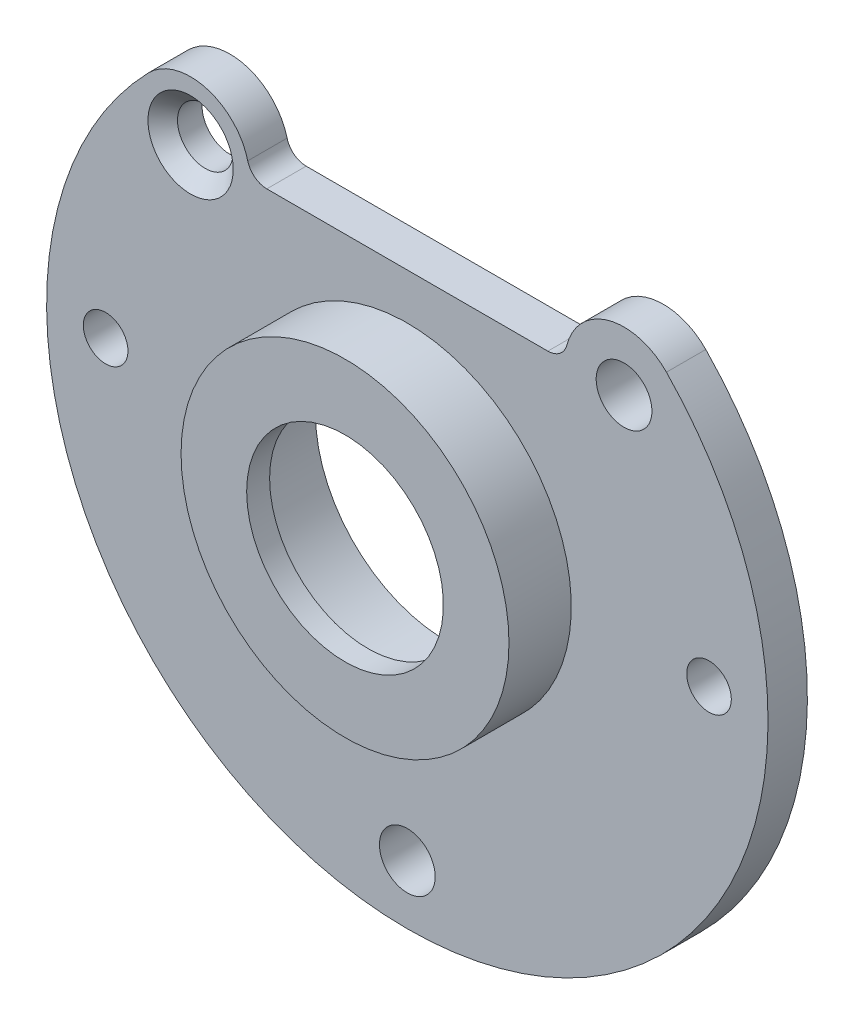
SolidWorks part; units mm, degrees
ref_plane "前视基准面" through (0, 0, 0) normal (0, 0, 1) x (1, 0, 0)
ref_plane "上视基准面" through (0, 0, 0) normal (0, 1, 0) x (1, 0, 0)
ref_plane "右视基准面" through (0, 0, 0) normal (1, 0, 0) x (0, 0, -1)
sketch "草图1" plane through (0, 0, 0) normal (0, 0, 1) x (1, 0, 0)
  line L0 (0, 0) -> (33.0454, 32) construction
  line L1 (0, 0) -> (0, 24.5594) construction
  line L2 (0, -55) -> (0, 55) construction
  line L3 (0, 0) -> (-33.0454, 32) construction
  line L4 (21.4265, 32) -> (-21.4265, 32)
  line L5 (55, 0) -> (-55, 0) construction
  arc A0 (-39.5108, 38.2609) -> (39.5108, 38.2609) centre (0, 0) ccw
  circle A1 centre (0, 0) radius 46 construction
  arc A2 (39.5108, 38.2609) -> (24.3312, 34.25) centre (33.0454, 32) ccw
  arc A3 (-39.5108, 38.2609) -> (-24.3312, 34.25) centre (-33.0454, 32) cw
  arc A4 (-26.58, 25.7391) -> (-38.6438, 24.9531) centre (-33.0454, 32) cw construction
  arc A5 (-38.6438, 24.9531) -> (-39.5108, 38.2609) centre (-33.0454, 32) cw construction
  arc A6 (-24.0454, 32) -> (-26.58, 25.7391) centre (-33.0454, 32) cw construction
  arc A7 (24.0454, 32) -> (26.58, 25.7391) centre (33.0454, 32) ccw construction
  arc A8 (26.58, 25.7391) -> (38.6438, 24.9531) centre (33.0454, 32) ccw construction
  arc A9 (38.6438, 24.9531) -> (39.5108, 38.2609) centre (33.0454, 32) ccw construction
  arc A10 (39.5108, 38.2609) -> (-39.5108, 38.2609) centre (0, 0) ccw construction
  arc A11 (21.4265, 32) -> (24.3312, 34.25) centre (21.4265, 35) ccw
  arc A12 (-24.3312, 34.25) -> (-21.4265, 32) centre (-21.4265, 35) ccw
  point P1 (11.1928, 32)
  point P14 (0, 32)
  dimension "D1" = 110
  dimension "D2" = 92
  dimension "D3" = 32
  dimension "D4" = 3
extrude "凸台-拉伸1" add sketch "草图1" along normal blind 6
sketch "草图2" plane through (0, 0, 6) normal (0, 0, 1) x (1, 0, 0)
  circle A0 centre (0, 0) radius 25
  dimension "D1" = 50
extrude "凸台-拉伸2" add sketch "草图2" along normal blind 9.5
sketch "草图3" plane through (0, 0, 0) normal (0, 0, -1) x (-1, 0, 0)
  circle A0 centre (0, 0) radius 20
  dimension "D1" = 40
extrude "切除-拉伸1" cut sketch "草图3" against normal blind 12
sketch "草图4" plane through (0, 0, 12) normal (0, 0, -1) x (-1, 0, 0)
  circle A0 centre (0, 0) radius 15
  dimension "D1" = 30
extrude "切除-拉伸2" cut sketch "草图4" against normal through all
hole_wizard "孔1" positions "草图5" profile "草图6" legacy
sketch "草图5" plane through (0, 0, 6) normal (0, 0, 1) x (1, 0, 0)
  circle A0 centre (0, 0) radius 46 construction
  point P0 (33.0454, 32)
  point P3 (0, -46)
sketch "草图6" plane through (33.0454, 32, 6) normal (1, 0, 0) x (0, -1, 0)
  line L0 (0, 0) -> (0, 93.98)
  line L1 (0, 93.98) -> (4.25, 93.98)
  line L2 (4.25, 93.98) -> (4.25, 0)
  line L3 (4.25, 0) -> (0, 0)
  line L4 (0, 110) -> (0, -10) construction
  dimension "直径" = 8.5
  dimension "深度" = 93.98
hole_wizard "M8 螺纹孔1" positions "草图7" profile "草图9" tap size "M8" standard "GB" end condition up to next
sketch "草图7" plane through (0, 0, 6) normal (0, 0, 1) x (1, 0, 0)
  line L0 (8.525, 0) -> (-8.525, 0) construction
  circle A0 centre (0, 0) radius 46 construction
  point P0 (46, 0)
  point P4 (-46, 0)
sketch "草图9" plane through (46, 0, 6) normal (1, 0, 0) x (0, -1, 0)
  line L0 (0, 0) -> (0, 6)
  line L1 (0, 6) -> (3.4, 6)
  line L2 (3.4, 6) -> (3.4, 0)
  line L5 (3.4, 0) -> (0, 0)
  line L11 (0, -6.35) -> (0, 107.95) construction
  dimension "通孔螺纹孔钻头直径" = 6.8
  dimension "通孔螺纹孔钻头深度" = 6
cosmetic thread "孔螺纹线1" parameters "D2"=8
cosmetic thread "孔螺纹线2" parameters "D2"=8
hole_wizard "Ø8.5 (8.5) 直径孔1" positions "草图10" profile "草图11" hole size "Ø8.5" standard "GB" end condition up to next
sketch "草图10" plane through (0, 0, 6) normal (0, 0, 1) x (1, 0, 0)
  point P0 (-33.0454, 32)
sketch "草图11" plane through (-33.0454, 32, 6) normal (1, 0, 0) x (0, -1, 0)
  line L0 (0, 0) -> (0, 6)
  line L1 (0, 6) -> (4.25, 6)
  line L2 (4.25, 6) -> (4.25, 2.25)
  line L3 (4.25, 2.25) -> (6.5, 0)
  line L5 (6.5, 0) -> (0, 0)
  line L6 (-4.25, 2.25) -> (-6.5, 0) construction
  line L11 (0, -6.35) -> (0, 107.95) construction
  dimension "通孔孔直径" = 8.5
  dimension "通孔孔深度" = 6
  dimension "近端锥形沉头孔直径" = 13
  dimension "近端锥形沉头孔角度" = 90
